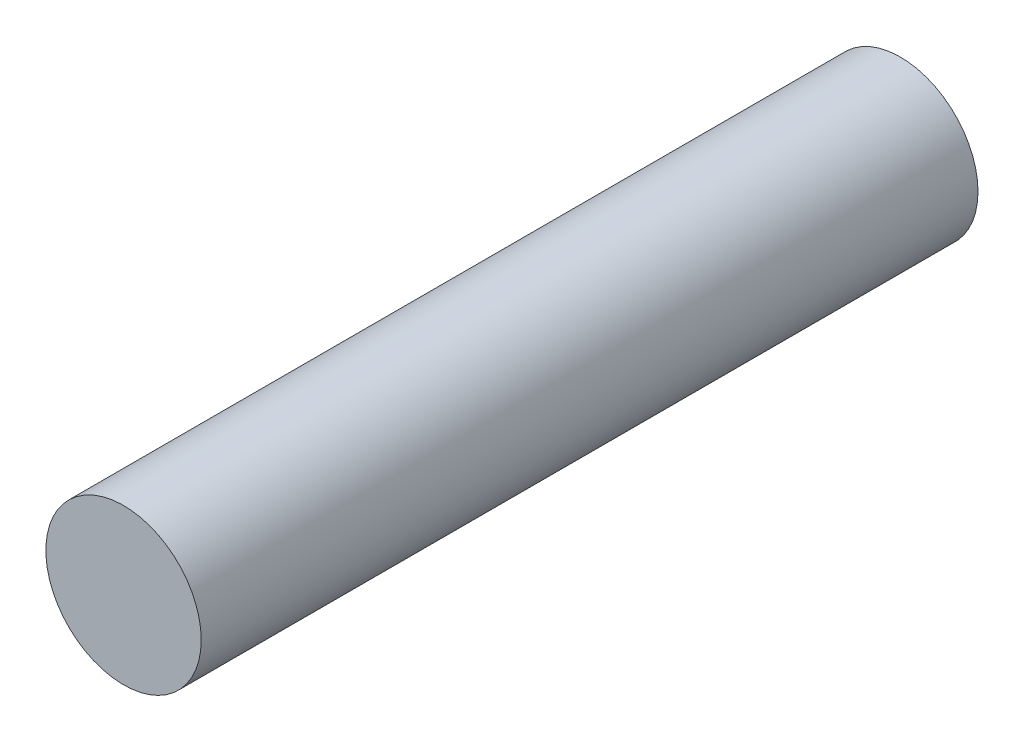
SolidWorks part; units mm, degrees
material "ABS"
ref_plane "Front Plane" through (0, 0, 0) normal (0, 0, 1) x (1, 0, 0)
ref_plane "Top Plane" through (0, 0, 0) normal (0, 1, 0) x (1, 0, 0)
ref_plane "Right Plane" through (0, 0, 0) normal (1, 0, 0) x (0, 0, -1)
sketch "Sketch1" plane through (0, 0, 0) normal (0, 0, 1) x (1, 0, 0)
  circle A1 centre (0, 0) radius 1.5875
extrude "Boss-Extrude1" add sketch "Sketch1" along normal blind 15.875
